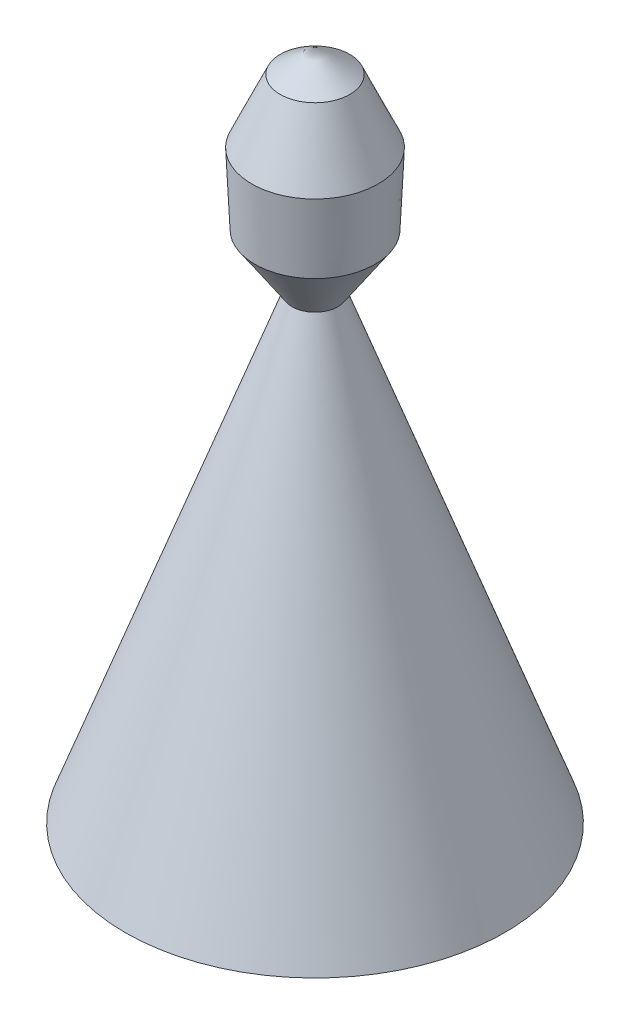
SolidWorks part; units mm, degrees
ref_plane "Front Plane" through (0, 0, 0) normal (0, 0, 1) x (1, 0, 0)
ref_plane "Top Plane" through (0, 0, 0) normal (0, 1, 0) x (1, 0, 0)
ref_plane "Right Plane" through (0, 0, 0) normal (1, 0, 0) x (0, 0, -1)
sketch "Sketch1" plane through (0, 0, 0) normal (0, 0, 1) x (1, 0, 0)
  line L0 (0, 0) -> (0, 4300) construction
  line L1 (0, 4300) -> (220, 4150)
  line L2 (220, 4150) -> (400, 3750)
  line L3 (400, 3750) -> (380, 3300)
  line L4 (380, 3300) -> (145, 2950)
  line L5 (145, 2950) -> (1200, 50)
  line L6 (1200, 50) -> (1170, 50)
  line L7 (1170, 50) -> (125, 2950)
  line L8 (125, 2950) -> (340, 3300)
  line L9 (340, 3300) -> (340, 3750)
  line L10 (340, 3750) -> (0, 3750)
  line L11 (0, 3750) -> (0, 4300)
revolve "Revolve1" add sketch "Sketch1" angle 360 about L0
sketch "Sketch2" plane through (0, 0, 0) normal (0, 0, 1) x (1, 0, 0)
  line L0 (0, 0) -> (0, 4300) construction
  circle A0 centre (1050, 400) radius 21.3063
  circle A1 centre (820, 1000) radius 25
  circle A2 centre (560, 1700) radius 25
  circle A3 centre (310, 2400) radius 25
revolve "Revolve2" add sketch "Sketch2" angle 360 about L0
